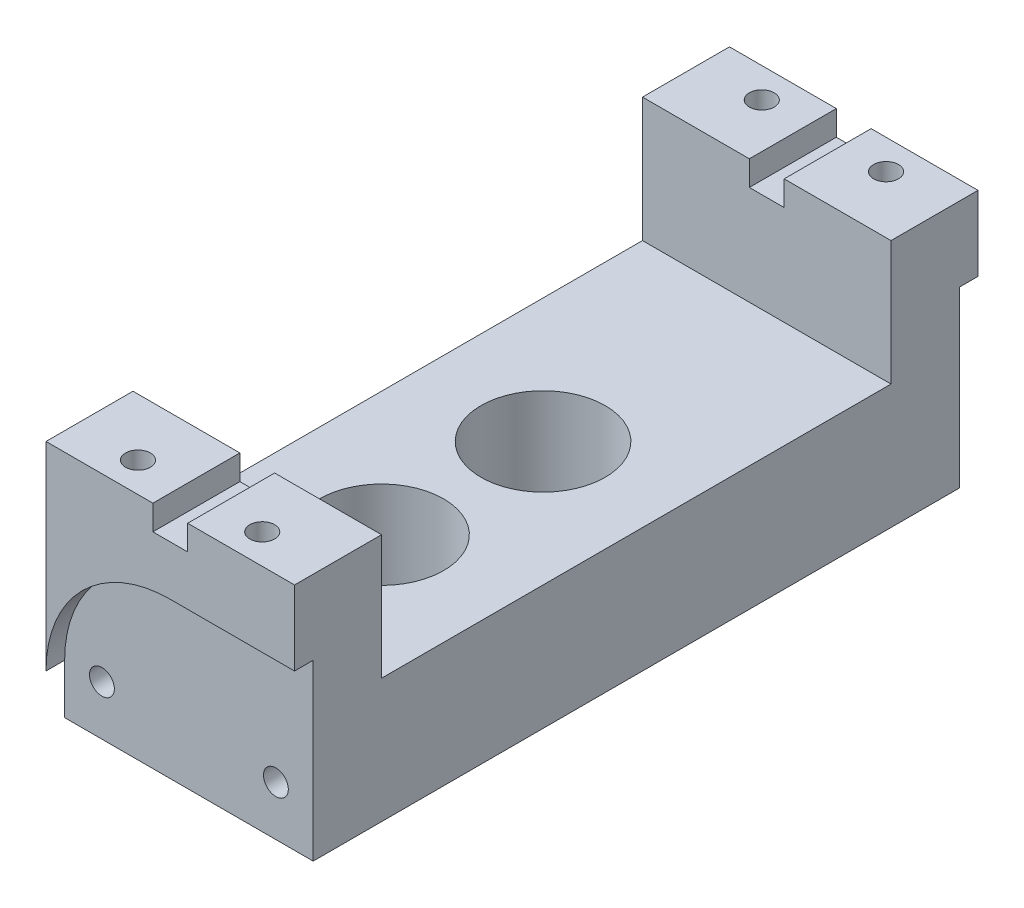
SolidWorks part; units mm, degrees
ref_plane "Спереди" through (0, 0, 0) normal (0, 0, 1) x (1, 0, 0)
ref_plane "Сверху" through (0, 0, 0) normal (0, 1, 0) x (1, 0, 0)
ref_plane "Справа" through (0, 0, 0) normal (1, 0, 0) x (0, 0, -1)
sketch "Эскиз1" plane through (0, 0, 0) normal (0, 1, 0) x (1, 0, 0)
  line L1 (0, 0) -> (20, 0)
  line L2 (0, 0) -> (0, 55)
  line L3 (0, 55) -> (20, 55)
  line L4 (20, 0) -> (20, 55)
  dimension "D1" = 55
  dimension "D2" = 20
extrude "Бобышка-Вытянуть1" add sketch "Эскиз1" along normal blind 20
sketch "Эскиз2" plane through (0, 20, 0) normal (0, 1, 0) x (1, 0, 0)
  line L0 (0, 55) -> (0, 0) construction
  line L3 (20, 0) -> (20, 55) construction
  line L4 (20, 48) -> (0, 48)
  line L7 (20, 48) -> (20, 7)
  line L8 (20, 7) -> (0, 7)
  line L9 (0, 48) -> (0, 7)
extrude "Вырез-Вытянуть1" cut sketch "Эскиз2" against normal blind 10
sketch "Эскиз3" plane through (0, 20, 0) normal (0, 1, 0) x (1, 0, 0)
  line L3 (20, 55) -> (0, 55) construction
  line L4 (11.4, 55) -> (8.6, 55)
  line L5 (8.6, 55) -> (8.6, 0)
  line L6 (0, 0) -> (20, 0) construction
  line L7 (8.6, 0) -> (11.4, 0)
  line L8 (11.4, 0) -> (11.4, 55)
extrude "Вырез-Вытянуть2" cut sketch "Эскиз3" against normal blind 2
sketch "Эскиз4" plane through (0, 20, 0) normal (0, 1, 0) x (1, 0, 0)
  line L0 (20, 48) -> (11.4, 48) construction
  line L1 (10, 55) -> (10, 0) construction
  line L2 (11.4, 55) -> (8.6, 55) construction
  line L3 (8.6, 0) -> (11.4, 0) construction
  line L4 (15, 52.6) -> (15, 2.4) construction
  line L5 (15, 52.6) -> (1.3177, 52.6) construction
  line L6 (4.1481, 53.6) -> (15, 53.6) construction
  line L7 (5, 53.6) -> (5, 0.2835) construction
  line L8 (15, 2.4) -> (1.862, 2.4) construction
  line L9 (11.4, 7) -> (20, 7) construction
  line L11 (15, 1.4) -> (5, 1.4) construction
  circle A0 centre (15, 52.6) radius 1
  circle A1 centre (5, 52.6) radius 1
  circle A2 centre (15, 2.4) radius 1
  circle A3 centre (5, 2.4) radius 1
  dimension "D1" = 2
  dimension "D4" = 10
  dimension "D5" = 4.6
  dimension "D6" = 2
  dimension "D2" = 4.6
  dimension "D3" = 5
extrude "Вырез-Вытянуть3" cut sketch "Эскиз4" against normal blind 4
sketch "Эскиз5" plane through (0, 0, 0) normal (0, -1, 0) x (1, 0, 0)
  line L0 (0, -55) -> (0, 0) construction
  line L1 (0, 0) -> (20, 0) construction
  line L2 (10, -17) -> (10, -30) construction
  circle A0 centre (10, -17) radius 5
  circle A1 centre (10, -30) radius 5
  dimension "D1" = 10
  dimension "D2" = 17
  dimension "D3" = 10
extrude "Вырез-Вытянуть4" cut sketch "Эскиз5" against normal through all
sketch "Эскиз6" plane through (0, 0, -55) normal (0, 0, -1) x (-1, 0, 0)
  line L0 (-20, 0) -> (0, 0) construction
  line L2 (-20, 20) -> (-20, 0) construction
  line L3 (-17, 4) -> (-3, 4) construction
  line L4 (-17, 5) -> (-3, 5) construction
  circle A0 centre (-17, 4) radius 1
  circle A1 centre (-3, 4) radius 1
  dimension "D1" = 2
  dimension "D2" = 4
  dimension "D3" = 3
  dimension "D4" = 14
extrude "Вырез-Вытянуть5" cut sketch "Эскиз6" against normal blind 7
sketch "Эскиз7" plane through (0, 0, 0) normal (0, 0, 1) x (1, 0, 0)
  line L0 (0, 0) -> (20, 0) construction
  line L1 (0, 20) -> (0, 0) construction
  line L2 (3, 4) -> (18.6811, 4) construction
  circle A0 centre (3, 4) radius 1
  circle A1 centre (17, 4) radius 1
  dimension "D1" = 4
  dimension "D3" = 14
  dimension "D2" = 3
extrude "Вырез-Вытянуть6" cut sketch "Эскиз7" against normal blind 7
sketch "Эскиз8" plane through (0, 0, -55) normal (0, 0, -1) x (-1, 0, 0)
  line L0 (-10, 14) -> (-20, 14)
  line L1 (0, 4) -> (0, 0)
  line L2 (0, 0) -> (-20, 0)
  line L3 (-20, 14) -> (-20, 0)
  line L4 (-20, 20) -> (-20, 0) construction
  arc A0 (0, 4) -> (-10, 14) centre (-10, 4) ccw
extrude "Вырез-Вытянуть7" cut sketch "Эскиз8" against normal blind 1.5
sketch "Эскиз9" plane through (0, 0, 0) normal (0, 0, 1) x (1, 0, 0)
  line L0 (0, 4) -> (0, 0)
  line L1 (0, 0) -> (20, 0)
  line L3 (10, 14) -> (20, 14)
  line L4 (20, 20) -> (20, 0) construction
  line L5 (20, 14) -> (20, 0)
  arc A0 (10, 14) -> (0, 4) centre (10, 4) ccw
extrude "Вырез-Вытянуть8" cut sketch "Эскиз9" against normal blind 1.5
